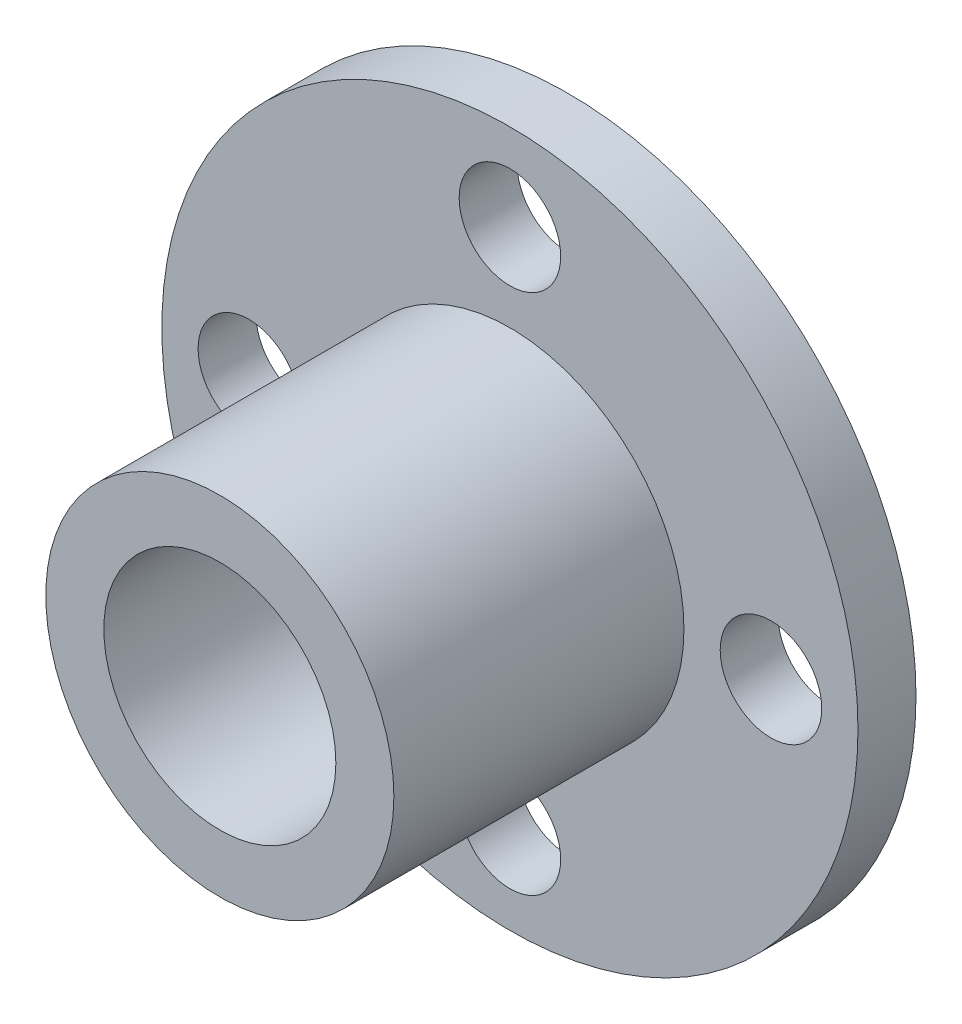
SolidWorks part; units mm, degrees
ref_plane "前视基准面" through (0, 0, 0) normal (0, 0, 1) x (1, 0, 0)
ref_plane "上视基准面" through (0, 0, 0) normal (0, 1, 0) x (1, 0, 0)
ref_plane "右视基准面" through (0, 0, 0) normal (1, 0, 0) x (0, 0, -1)
other "Configuration Table"
sketch "草图1" plane through (0, 0, 0) normal (0, 0, 1) x (1, 0, 0)
  circle A0 centre (0, 0) radius 12
  circle A1 centre (0, 0) radius 6 construction
  circle A2 centre (0, 0) radius 4
  dimension "D1" = 24
  dimension "D2" = 12
  dimension "D3" = 8
extrude "凸台-拉伸1" add sketch "草图1" along normal blind 2
sketch "草图2" plane through (0, 0, 2) normal (0, 0, 1) x (1, 0, 0)
  circle A0 centre (0, 0) radius 4 construction
  circle A1 centre (0, 0) radius 4
  circle A2 centre (0, 0) radius 6
  dimension "D1" = 12
extrude "凸台-拉伸3" add sketch "草图2" along normal blind 10
sketch "草图4" plane through (0, 0, 0) normal (0, 0, -1) x (-1, 0, 0)
  line L0 (0, 0) -> (0, 9) construction
  line L1 (0, 0) -> (9, 0) construction
  line L2 (0, 0) -> (0, -9) construction
  line L3 (0, 0) -> (-9, 0) construction
  circle A0 centre (0, 0) radius 9 construction
  circle A2 centre (9, 0) radius 1.75
  circle A3 centre (0, 9) radius 1.75
  circle A4 centre (-9, 0) radius 1.75
  circle A5 centre (0, -9) radius 1.75
  dimension "D3" = 3.5
  dimension "D4" = 18
  dimension "D1" = 90
  dimension "D2" = 90
extrude "切除-拉伸1" cut sketch "草图4" against normal blind 16.7
sketch "草图3" plane through (0, 0, 0) normal (0, 0, -1) x (-1, 0, 0)
  circle A0 centre (0, 0) radius 9 construction
  circle A3 centre (0, -9) radius 2.7
  dimension "D1" = 18
  dimension "D2" = 5.4
